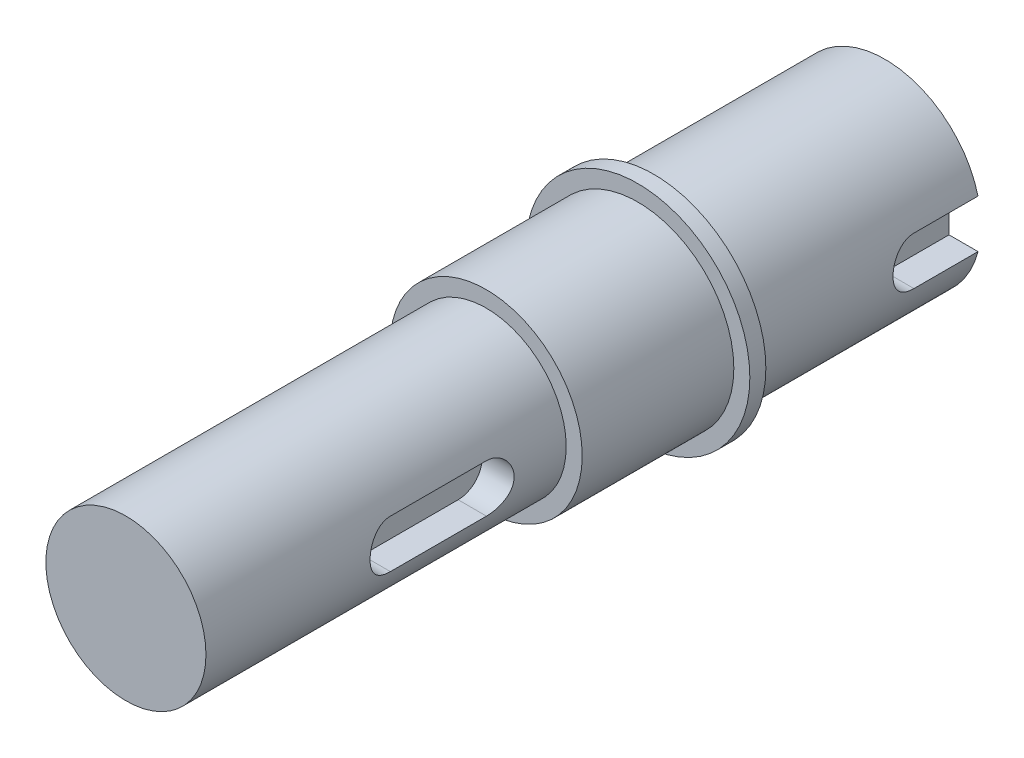
SolidWorks part; units mm, degrees
ref_plane "前视基准面" through (0, 0, 0) normal (0, 0, 1) x (1, 0, 0)
ref_plane "上视基准面" through (0, 0, 0) normal (0, 1, 0) x (1, 0, 0)
ref_plane "右视基准面" through (0, 0, 0) normal (1, 0, 0) x (0, 0, -1)
sketch "草图1" plane through (0, 0, 0) normal (0, 0, 1) x (1, 0, 0)
  circle A0 centre (0, 0) radius 5
  dimension "D1" = 10
extrude "凸台-拉伸1" add sketch "草图1" along normal blind 15.5
sketch "草图2" plane through (0, 0, 0) normal (0, 0, -1) x (-1, 0, 0)
  circle A0 centre (0, 0) radius 6
  dimension "D1" = 12
extrude "凸台-拉伸2" add sketch "草图2" along normal blind 17.91
ref_plane "基准面4" through (5, 0, 0) normal (1, 0, 0) x (0, 0, -1)
sketch "草图3" plane through (5, 0, 0) normal (1, 0, 0) x (0, 0, -1)
  line L0 (-7.75, -5) -> (-7.75, 5) construction
  line L1 (-15.5, -5) -> (0, -5) construction
  line L2 (0, 5) -> (-15.5, 5) construction
  line L3 (-10.75, 0) -> (-4.75, 0) construction
  line L4 (-10.75, 1.5) -> (-4.75, 1.5)
  line L5 (-10.75, -1.5) -> (-4.75, -1.5)
  arc A0 (-10.75, 1.5) -> (-10.75, -1.5) centre (-10.75, 0) ccw
  arc A1 (-4.75, -1.5) -> (-4.75, 1.5) centre (-4.75, 0) ccw
  point P8 (-7.75, 0)
  dimension "D1" = 3
  dimension "D2" = 6
extrude "切除-拉伸1" cut sketch "草图3" against normal blind 2
sketch "草图4" plane through (0, 0, 15.5) normal (0, 0, 1) x (1, 0, 0)
  circle A0 centre (0, 0) radius 5
  dimension "D1" = 10
extrude "凸台-拉伸3" add sketch "草图4" along normal blind 7
sketch "草图5" plane through (0, 0, -17.91) normal (0, 0, -1) x (-1, 0, 0)
  circle A0 centre (0, 0) radius 7
  circle A1 centre (0, 0) radius 6 construction
  dimension "D1" = 1
extrude "凸台-拉伸4" add sketch "草图5" along normal blind 1
sketch "草图6" plane through (0, 0, -18.91) normal (0, 0, -1) x (-1, 0, 0)
  circle A0 centre (0, 0) radius 6
  dimension "D1" = 12
extrude "凸台-拉伸5" add sketch "草图6" along normal blind 6
ref_plane "基准面5" through (0, 6, 0) normal (0, 1, 0) x (1, 0, 0)
ref_plane "基准面6" through (6, 0, 0) normal (1, 0, 0) x (0, 0, -1)
sketch "草图7" plane through (6, 0, 0) normal (1, 0, 0) x (0, 0, -1)
  line L0 (20.91, 0) -> (24.91, 0) construction
  line L3 (24.91, -6) -> (24.91, 6) construction
  line L4 (20.91, 1.5) -> (24.91, 1.5)
  line L5 (20.91, -1.5) -> (24.91, -1.5)
  arc A2 (20.91, 1.5) -> (20.91, -1.5) centre (20.91, 0) ccw
  arc A3 (24.91, -1.5) -> (24.91, 1.5) centre (24.91, 0) ccw
  point P4 (22.91, 0)
  dimension "D1" = 1.5
  dimension "D2" = 4
extrude "切除-拉伸2" cut sketch "草图7" against normal blind 2
sketch "草图8" plane through (0, 0, -24.91) normal (0, 0, -1) x (-1, 0, 0)
  circle A0 centre (0, 0) radius 1.25
  dimension "D1" = 2.5
extrude "切除-拉伸3" cut sketch "草图8" against normal blind 10
cosmetic thread "装饰螺纹线1" parameters "D2"=3
ref_plane "基准面7" through (0, 0, -10.47) normal (0, 0, 1) x (1, 0, 0)
sketch "草图9" plane through (0, 0, -10.47) normal (0, 0, 1) x (1, 0, 0)
  circle A0 centre (0, 0) radius 7
  circle A1 centre (0, 0) radius 7 construction
extrude "凸台-拉伸6" add sketch "草图9" along normal blind 1
sketch "草图10" plane through (0, 0, -18.91) normal (0, 0, -1) x (-1, 0, 0)
  circle A0 centre (0, 0) radius 7
  circle A1 centre (0, 0) radius 7 construction
  circle A2 centre (0, 0) radius 6
  circle A3 centre (0, 0) radius 6 construction
extrude "切除-拉伸5" cut sketch "草图10" against normal blind 1
